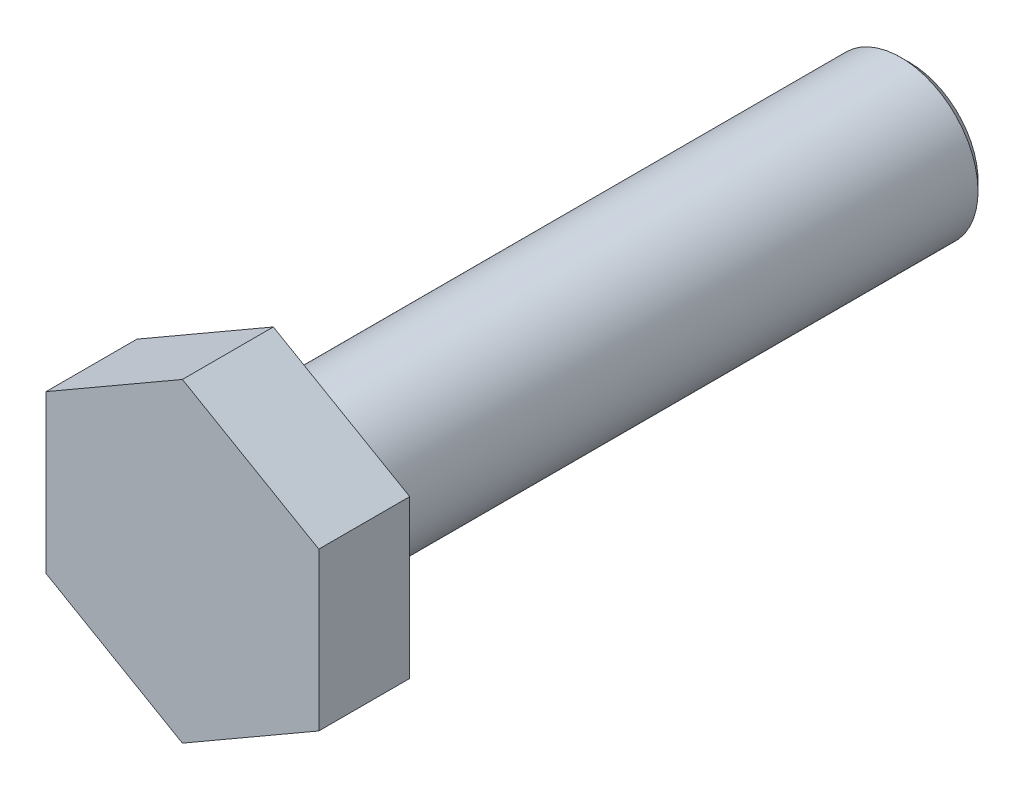
SolidWorks part; units mm, degrees
ref_plane "Plano frontal" through (0, 0, 0) normal (0, 0, 1) x (1, 0, 0)
ref_plane "Plano superior" through (0, 0, 0) normal (0, 1, 0) x (1, 0, 0)
ref_plane "Plano direito" through (0, 0, 0) normal (1, 0, 0) x (0, 0, -1)
sketch "Esboço1" plane through (0, 0, 0) normal (0, 0, 1) x (1, 0, 0)
  line L7 (0, 17.3205) -> (-15, 8.6603)
  line L8 (15, 8.6603) -> (0, 17.3205)
  line L9 (15, -8.6603) -> (15, 8.6603)
  line L10 (0, -17.3205) -> (15, -8.6603)
  line L11 (-15, -8.6603) -> (0, -17.3205)
  line L12 (-15, 8.6603) -> (-15, -8.6603)
  line L13 (0, 17.3205) -> (-15, 8.6603)
  line L14 (15, 8.6603) -> (0, 17.3205)
  line L15 (15, -8.6603) -> (15, 8.6603)
  line L16 (0, -17.3205) -> (15, -8.6603)
  line L17 (-15, -8.6603) -> (0, -17.3205)
  line L18 (-15, 8.6603) -> (-15, -8.6603)
  dimension "D1" = 0
extrude "Ressalto-extrusão1" add sketch "Esboço1" against normal up to vertex (10 mm away)
sketch "Esboço2" plane through (0, 0, -10) normal (0, 0, -1) x (-1, 0, 0)
  circle A0 centre (0, 0) radius 8.5
  dimension "D1" = 17
extrude "Ressalto-extrusão2" add sketch "Esboço2" along normal blind 70
sketch "Esboço3" plane through (0, 0, -80) normal (0, 0, -1) x (-1, 0, 0)
  line L0 (3, -11.3) -> (3, -7.953) construction
  line L1 (3, -8.7853) -> (-3, -8.7853)
  line L2 (3, -8.7853) -> (3, -5.3)
  line L3 (3, -5.3) -> (-3, -5.3)
  line L4 (-3, -8.7853) -> (-3, -5.3)
  line L5 (-3, -7.953) -> (-3, -11.3) construction
  line L6 (-3, -11.3) -> (3, -11.3) construction
  dimension "D1" = 6
extrude "Corte-extrusão1" cut sketch "Esboço3" against normal blind 40
fillet "Filete1" radius 2 2 edges at (-3, -6.6265, -40) (3, -6.6265, -40)
chamfer "Chanfro1" distance 1 angle 45 1 edges at (0, 8.5, -80)
sketch "Sketch1" plane through (0, 0, -80) normal (0, 0, -1) x (-1, 0, 0)
  circle A0 centre (0, 0) radius 8.5
